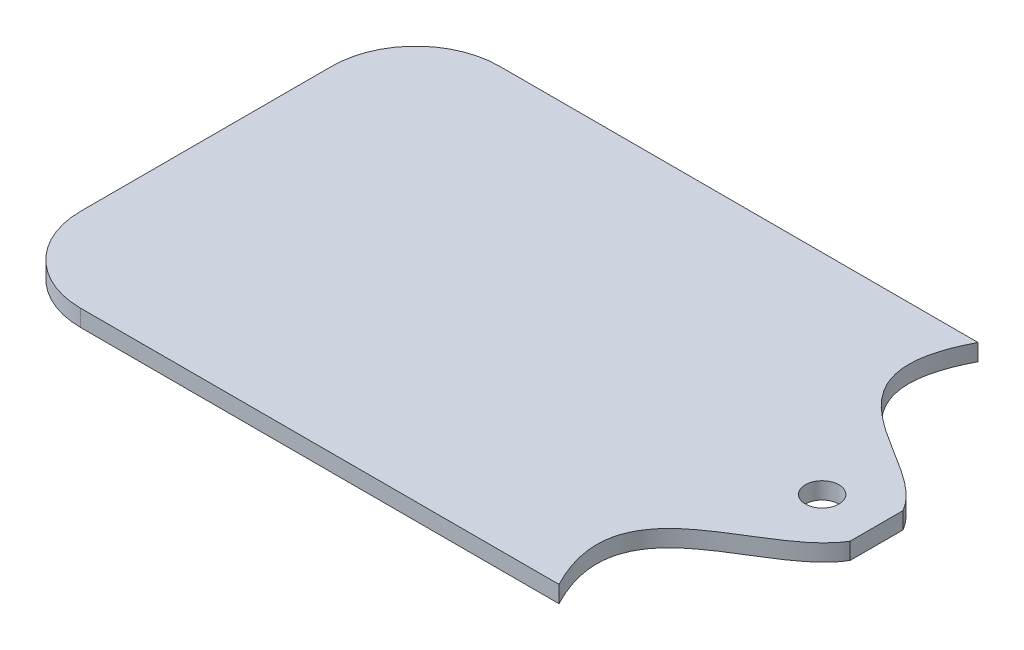
SolidWorks part; units mm, degrees
ref_plane "Front Plane" through (0, 0, 0) normal (0, 0, 1) x (1, 0, 0)
ref_plane "Top Plane" through (0, 0, 0) normal (0, 1, 0) x (1, 0, 0)
ref_plane "Right Plane" through (0, 0, 0) normal (1, 0, 0) x (0, 0, -1)
sketch "Sketch1" plane through (0, 0, 0) normal (0, 1, 0) x (1, 0, 0)
  line L0 (335, 0) -> (0, 0) construction
  line L1 (-300, 250) -> (270.9877, 250)
  line L2 (-400, 150) -> (-400, -150)
  line L3 (-300, -250) -> (270.9877, -250)
  line L4 (400, 31.5067) -> (400, -31.5067)
  line L5 (-400, 250) -> (256.5974, -160.3734) construction
  line L6 (-400, -250) -> (256.5974, 160.3734) construction
  circle A0 centre (335, 0) radius 20
  arc A1 (-300, 250) -> (-400, 150) centre (-300, 150) ccw
  arc A2 (-400, -150) -> (-300, -250) centre (-300, -150) ccw
  spline S0 degree 3 poles (270.9877, -250) (197.7229, -110.465) (360.73, -99.4978) (400, -31.5067) knots 0 0 0 0 0.797109 0.797109 0.797109 0.797109
  spline S1 degree 3 poles (270.9877, 250) (197.7229, 110.465) (360.73, 99.4978) (400, 31.5067) knots 0 0 0 0 0.797109 0.797109 0.797109 0.797109
  point P0 (0, 0)
  dimension "D3" = 40
  dimension "D1" = 100
  dimension "D4" = 335
extrude "Boss-Extrude1" add sketch "Sketch1" along normal blind 20
sketch "Sketch2" plane through (0, 0, 0) normal (0, -1, 0) x (1, 0, 0)
  line L0 (270.9877, -250) -> (270.9877, 250) construction
  line L1 (270.9877, -250) -> (-400, -250) construction
  line L2 (-400, -250) -> (-400, 250) construction
  line L3 (-400, 250) -> (270.9877, 250) construction
  line L4 (-64.5062, -250) -> (-64.5062, 250) construction
  line L6 (-34.5062, -190) -> (-94.5062, -190)
  line L7 (-34.5062, -190) -> (-34.5062, -250)
  line L8 (-34.5062, -250) -> (-94.5062, -250)
  line L9 (-94.5062, -190) -> (-94.5062, -250)
  line L10 (-34.5062, -190) -> (-94.5062, -250) construction
  line L11 (-34.5062, -250) -> (-94.5062, -190) construction
  point P9 (-64.5062, -220)
  dimension "D1" = 60
  dimension "D2" = 60
  dimension "D3" = 335.4938
extrude "Boss-Extrude2" add sketch "Sketch2" along normal blind 20
sketch "Sketch3" plane through (0, 0, -250) normal (0, 0, -1) x (-1, 0, 0)
  line L0 (64.5062, -20) -> (64.5062, 20) construction
  line L1 (94.5062, -20) -> (34.5062, -20) construction
  line L2 (-270.9877, 20) -> (300, 20) construction
  circle A0 centre (64.5062, 0) radius 5
  dimension "D1" = 10
extrude "Cut-Extrude1" cut sketch "Sketch3" against normal blind 20
